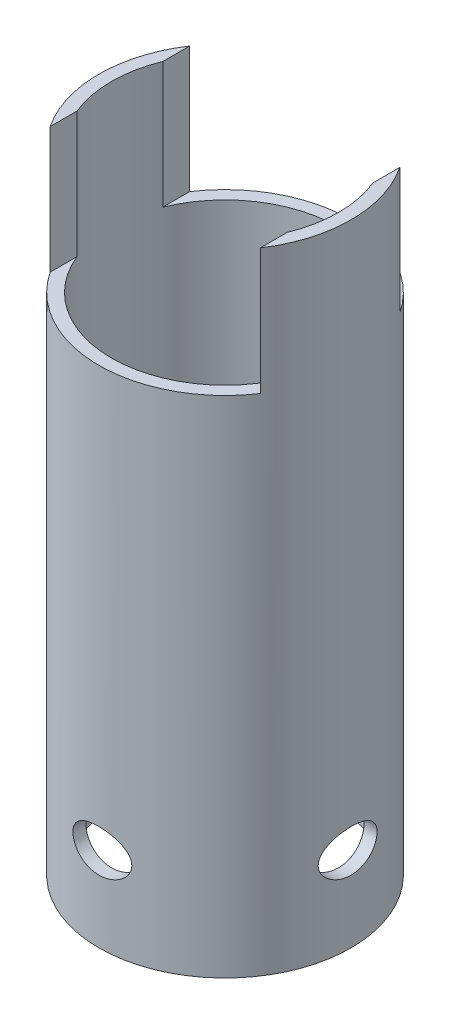
SolidWorks part; units mm, degrees
ref_plane "Front Plane" through (0, 0, 0) normal (0, 0, 1) x (1, 0, 0)
ref_plane "Top Plane" through (0, 0, 0) normal (0, 1, 0) x (1, 0, 0)
ref_plane "Right Plane" through (0, 0, 0) normal (1, 0, 0) x (0, 0, -1)
sketch "Sketch2" plane through (0, 0, 0) normal (0, 1, 0) x (1, 0, 0)
  circle A0 centre (0, 0) radius 15
  circle A1 centre (0, 0) radius 13.5
  dimension "D1" = 30
  dimension "D2" = 27
extrude "Boss-Extrude2" add sketch "Sketch2" along normal blind 75
sketch "Sketch4" plane through (0, 0, 0) normal (0, 0, 1) x (1, 0, 0)
  ellipse E0 centre (0, 10) end of major axis (3.5, 10) minor radius 2.5
  dimension "D2" = 10
  dimension "D3" = 3.5
  dimension "D4" = 2.5
  dimension "D5" = 3.5
extrude "Cut-Extrude1" cut sketch "Sketch4" against normal through all both and the other way through all contours E0
sketch "Sketch5" plane through (0, 0, 0) normal (1, 0, 0) x (0, 0, -1)
  ellipse E0 centre (0, 10) end of major axis (-3.5, 10) minor radius 2.5
  dimension "D2" = 10
  dimension "D3" = 3.5
  dimension "D4" = 2.5
  dimension "D5" = 2.5
extrude "Cut-Extrude2" cut sketch "Sketch5" against normal through all both and the other way through all
sketch "Sketch6" plane through (0, 0, 0) normal (0, 0, 1) x (1, 0, 0)
  line L0 (15, 75) -> (-15, 75) construction
  line L1 (-12.5, 75) -> (12.5, 75)
  line L2 (-12.5, 75) -> (-12.5, 60)
  line L3 (-12.5, 60) -> (12.5, 60)
  line L4 (12.5, 75) -> (12.5, 60)
  dimension "D1" = 25
  dimension "D2" = 2.5
  dimension "D3" = 15
extrude "Cut-Extrude3" cut sketch "Sketch6" against normal through all both and the other way through all
